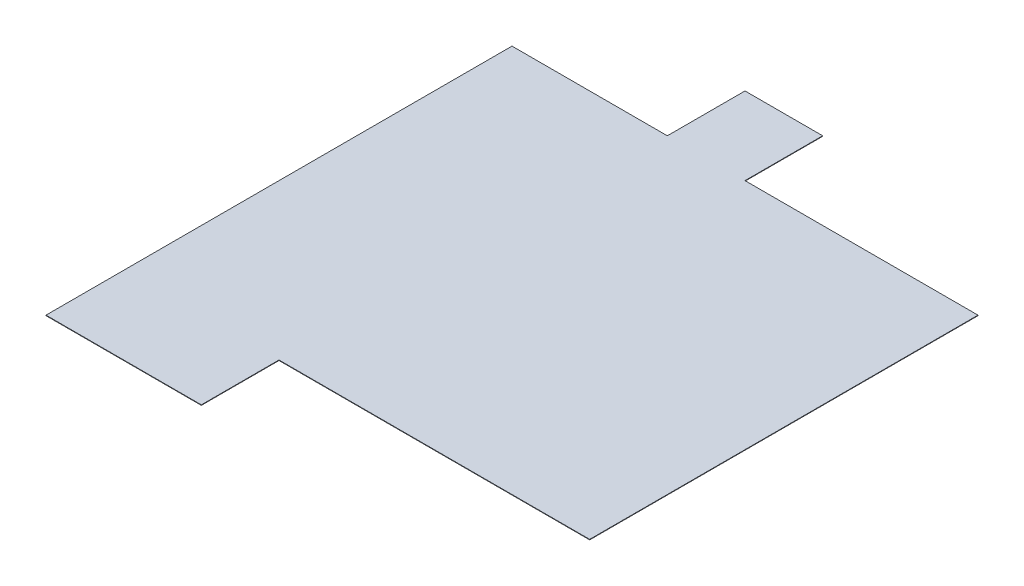
SolidWorks part; units mm, degrees
ref_plane "前视基准面" through (0, 0, 0) normal (0, 0, 1) x (1, 0, 0)
ref_plane "上视基准面" through (0, 0, 0) normal (0, 1, 0) x (1, 0, 0)
ref_plane "右视基准面" through (0, 0, 0) normal (1, 0, 0) x (0, 0, -1)
sketch "草图1" plane through (0, 0, 0) normal (0, 1, 0) x (1, 0, 0)
  line L5 (-2400, 2800) -> (2400, 2800)
  line L6 (-2400, 2800) -> (-2400, -2800)
  line L7 (-2400, -2800) -> (2400, -2800)
  line L8 (2400, 2800) -> (2400, -2800)
  line L9 (0, -2800) -> (0, 2800) construction
  line L10 (-2400, 0) -> (2400, 0) construction
  line L15 (-2400, 2000) -> (2400, 2000) construction
  line L17 (-2400, 1200) -> (2400, 1200) construction
  line L19 (-2400, 400) -> (2400, 400) construction
  line L20 (-2400, -400) -> (2400, -400) construction
  line L21 (-2400, -1200) -> (2400, -1200) construction
  line L22 (-2400, -2000) -> (2400, -2000) construction
  line L23 (-1600, 2800) -> (-1600, -2800) construction
  line L24 (-800, 2800) -> (-800, -2800) construction
  line L25 (0, 2800) -> (0, -2800) construction
  line L26 (800, 2800) -> (800, -2800) construction
  line L27 (1600, 2800) -> (1600, -2800) construction
  point P0 (0, 0)
  dimension "D1" = 4800
  dimension "D2" = 5600
  dimension "D3" = 800
  dimension "D4" = 6
  dimension "D5" = 1600
  dimension "D6" = 800
  dimension "D7" = 5
  dimension "D8" = 1600
extrude "凸台-拉伸1" add sketch "草图1" along normal blind 5
sketch "草图2" plane through (0, 0, 0) normal (0, 1, 0) x (1, 0, 0)
  line L0 (-2400, -2800) -> (2400, -2800) construction
  line L1 (2400, 2800) -> (2400, -2800) construction
  line L2 (-2400, -1200) -> (2400, -1200) construction
  line L3 (-800, 2800) -> (-800, -2800) construction
  line L4 (-800, -2800) -> (2400, -2800)
  line L5 (2400, -1200) -> (2400, -2800)
  line L6 (-800, -1200) -> (2400, -1200)
  line L7 (-800, -1200) -> (-800, -2000)
  line L8 (-2400, -2000) -> (-800, -2000)
  line L9 (-2400, -2000) -> (-2400, -2800)
  line L10 (-2400, -2800) -> (-800, -2800)
extrude "切除-拉伸2" cut sketch "草图2" along normal blind 5
sketch "草图3" plane through (0, 0, 0) normal (0, 1, 0) x (1, 0, 0)
  line L0 (-800, 2800) -> (-800, 3600)
  line L1 (-800, 3600) -> (0, 3600)
  line L2 (0, 3600) -> (0, 2800)
  line L3 (0, 2800) -> (-800, 2800)
  dimension "D1" = 800
extrude "凸台-拉伸2" add sketch "草图3" along normal blind 5
